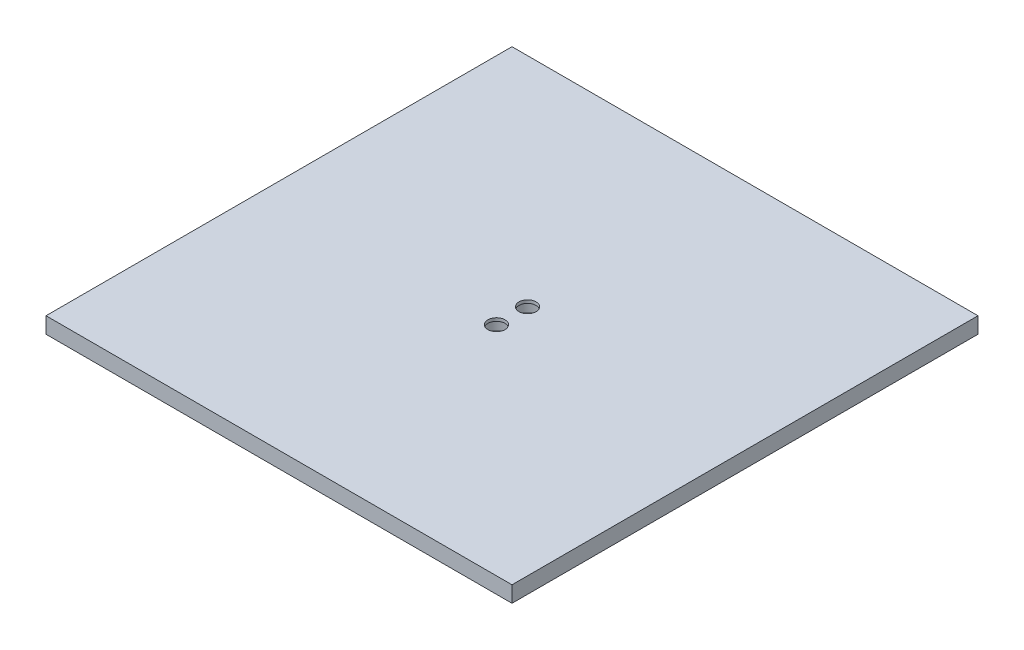
SolidWorks part; units mm, degrees
ref_plane "Front Plane" through (0, 0, 0) normal (0, 0, 1) x (1, 0, 0)
ref_plane "Top Plane" through (0, 0, 0) normal (0, 1, 0) x (1, 0, 0)
ref_plane "Right Plane" through (0, 0, 0) normal (1, 0, 0) x (0, 0, -1)
sketch "Sketch1" plane through (0, 0, 0) normal (0, 1, 0) x (1, 0, 0)
  line L1 (0, 0) -> (90, 0)
  line L2 (0, 0) -> (0, 90)
  line L3 (0, 90) -> (90, 90)
  line L4 (90, 0) -> (90, 90)
  dimension "D1" = 90
  dimension "D2" = 90
extrude "Boss-Extrude1" add sketch "Sketch1" against normal blind 3.1
sketch "Sketch2" plane through (0, -3.1, 0) normal (0, -1, 0) x (1, 0, 0)
  line L0 (0, -45) -> (90, -45) construction
  line L1 (0, -90) -> (0, 0) construction
  line L2 (90, 0) -> (90, -90) construction
  line L3 (45, 0) -> (45, -90) construction
  line L4 (0, 0) -> (90, 0) construction
  line L5 (90, -90) -> (0, -90) construction
  circle A0 centre (45, -42) radius 1.65
  circle A1 centre (45, -48) radius 1.65
  dimension "D1" = 3.3
  dimension "D2" = 3.3
  dimension "D3" = 6
  dimension "D4" = 42
extrude "Cut-Extrude1" cut sketch "Sketch2" against normal through all
sketch "Sketch5" plane through (0, -3.1, 0) normal (0, -1, 0) x (1, 0, 0)
  circle A0 centre (45, -42) radius 2.95
  circle A1 centre (45, -48) radius 2.95
  dimension "D1" = 5.9
  dimension "D2" = 5.9
extrude "Cut-Extrude2" cut sketch "Sketch5" against normal blind 2.5
